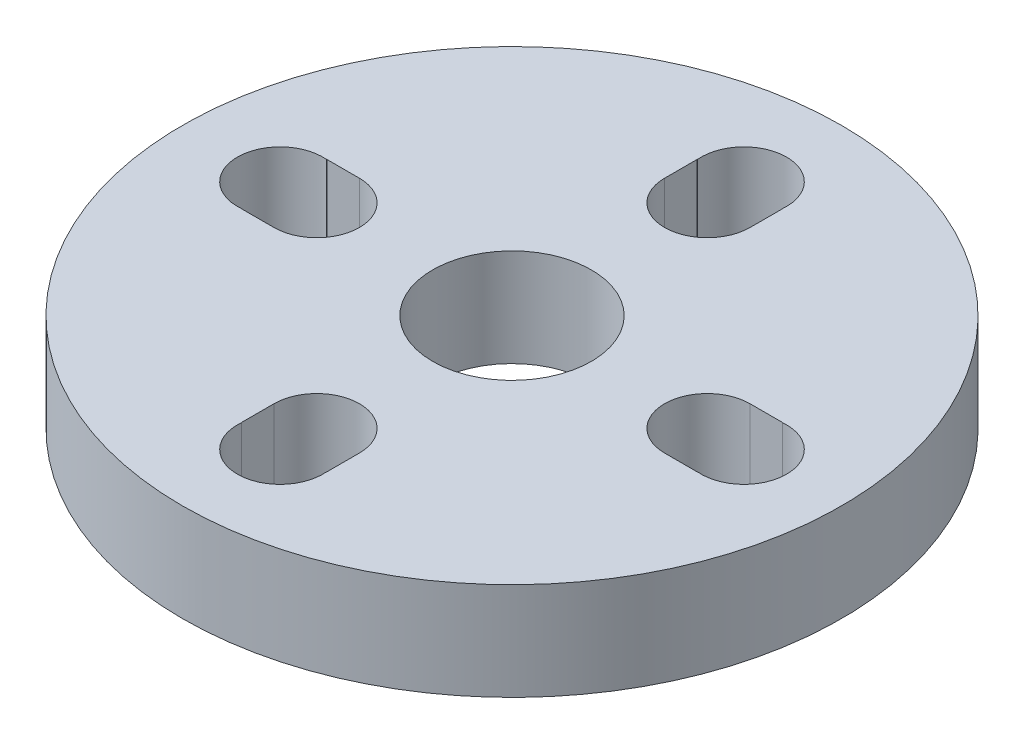
SolidWorks part; units mm, degrees
ref_plane "Front Plane" through (0, 0, 0) normal (0, 0, 1) x (1, 0, 0)
ref_plane "Top Plane" through (0, 0, 0) normal (0, 1, 0) x (1, 0, 0)
ref_plane "Right Plane" through (0, 0, 0) normal (1, 0, 0) x (0, 0, -1)
sketch "Sketch1" plane through (0, 0, 0) normal (0, 1, 0) x (1, 0, 0)
  circle A0 centre (0, 0) radius 13.5
  dimension "D1" = 27
extrude "Boss-Extrude1" add sketch "Sketch1" along normal blind 4
sketch "Sketch2" plane through (0, 4, 0) normal (0, 1, 0) x (1, 0, 0)
  line L0 (-13.5, 0) -> (13.5, 0) construction
  line L1 (0, 13.5) -> (0, -13.5) construction
  line L2 (-9.5, 1.75) -> (-8, 1.75)
  line L3 (-9.5, -1.75) -> (-8, -1.75)
  line L4 (0, 0) -> (9.5459, 9.5459) construction
  line L5 (9.5, -1.75) -> (8, -1.75)
  line L6 (9.5, 1.75) -> (8, 1.75)
  line L7 (-1.75, -9.5) -> (-1.75, -8)
  line L8 (1.75, -9.5) -> (1.75, -8)
  line L9 (1.75, 9.5) -> (1.75, 8)
  line L10 (-1.75, 9.5) -> (-1.75, 8)
  circle A0 centre (0, 0) radius 8
  circle A1 centre (0, 0) radius 9.5
  circle A2 centre (0, 0) radius 13.5 construction
  circle A3 centre (-9.5, 0) radius 1.75
  circle A4 centre (-8, 0) radius 1.75
  circle A5 centre (8, 0) radius 1.75
  circle A6 centre (9.5, 0) radius 1.75
  circle A7 centre (0, -8) radius 1.75
  circle A8 centre (0, -9.5) radius 1.75
  circle A9 centre (0, 8) radius 1.75
  circle A10 centre (0, 9.5) radius 1.75
  circle A11 centre (0, 0) radius 3.25
  dimension "D1" = 19
  dimension "D2" = 16
  dimension "D3" = 3.5
  dimension "D5" = 6.5
  dimension "D4" = 45
extrude "Cut-Extrude1" cut sketch "Sketch2" against normal up to next contours A4 A3 A1 L3 | A4 L2 A1 A3 | A10 A9 L9 A1 | A10 A1 L10 A9 | A1 A6 A5 L5 | A5 A6 A1 L6 | A7 A8 A1 L8 | A1 A8 A7 L7 | A11
